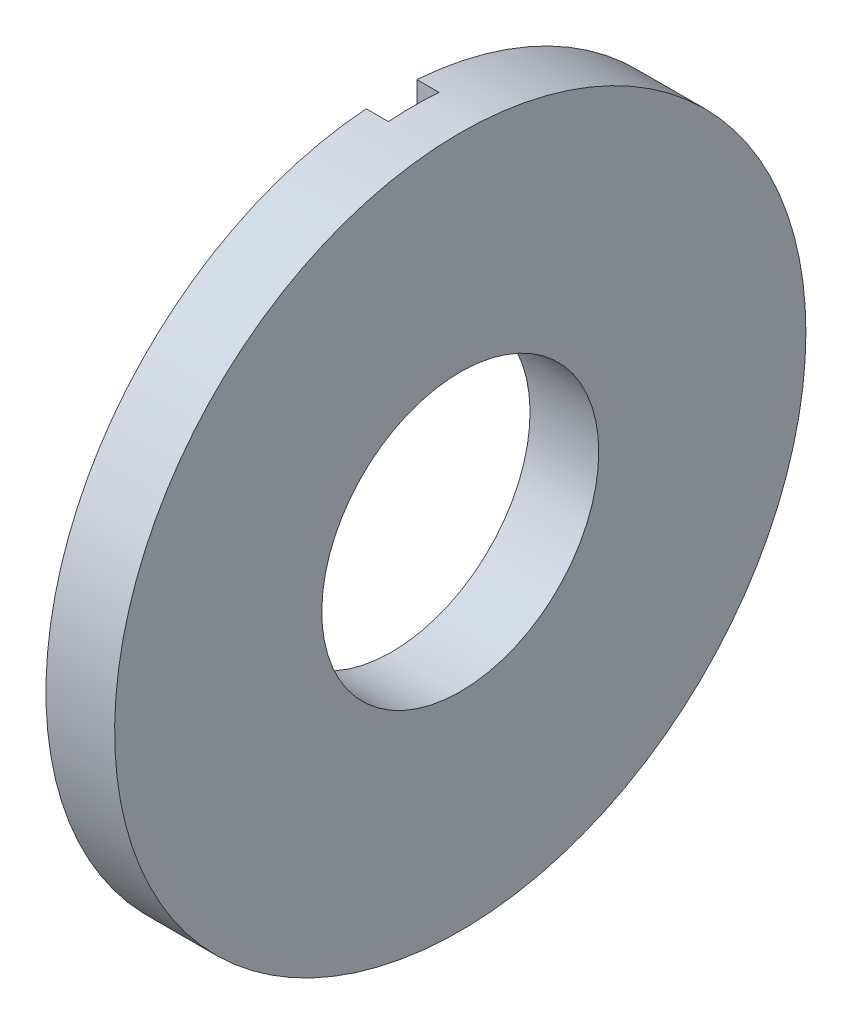
SolidWorks part; units mm, degrees
ref_plane "Front Plane" through (0, 0, 0) normal (0, 0, 1) x (1, 0, 0)
ref_plane "Top Plane" through (0, 0, 0) normal (0, 1, 0) x (1, 0, 0)
ref_plane "Right Plane" through (0, 0, 0) normal (1, 0, 0) x (0, 0, -1)
sketch "Sketch3" plane through (0, 0, 0) normal (0, 0, 1) x (1, 0, 0)
  line L0 (-0.3937, 0) -> (0.3937, 0) construction
  line L1 (0, -3.9624) -> (0, 3.9624) construction
  line L2 (0, -1.5875) -> (0, 1.5875) construction
  line L4 (0.3937, -3.9624) -> (-0.3937, -3.9624)
  line L5 (0.3937, -3.9624) -> (0.3937, 3.9624)
  line L6 (0.3937, 3.9624) -> (-0.3937, 3.9624)
  line L7 (-0.3937, -3.9624) -> (-0.3937, 3.9624)
  line L8 (0, 3.9624) -> (0, -3.9624) construction
  line L9 (0.3937, 0) -> (-0.3937, 0) construction
  point P0 (0, 0)
  point P4 (0, 0)
  point P8 (0, 0)
  point P11 (0, 0)
  dimension "Thickness" = 0.7874
sketch "Sketch1" plane through (0, 0, 0) normal (1, 0, 0) x (0, 0, -1)
  circle A0 centre (0, 0) radius 3.9624
  circle A1 centre (0, 0) radius 1.5875
extrude "Boss-Extrude1" add sketch "Sketch1" along normal mid plane 0.7874
sketch "Sketch4" plane through (-0.3937, 0, 0) normal (-1, 0, 0) x (0, 0, 1)
  line L0 (0, -3.9624) -> (0, 3.9624) construction
  point P0 (0, -1.5875)
sketch "Sketch5" plane through (-0.3937, 0, 0) normal (-1, 0, 0) x (0, 0, 1)
  line L0 (-0.2902, 0) -> (0.2902, 0)
  line L1 (0.2902, 0) -> (0.2902, 3.9624)
  line L2 (-0.2902, 0) -> (-0.2902, 3.9624)
  line L3 (-0.2902, 3.9624) -> (0.2902, 3.9624)
  circle A0 centre (0, 0) radius 3.9624 construction
  point P4 (0, 0)
extrude "Cut-Extrude1" cut sketch "Sketch5" against normal blind 0.254
equation "\"D1@Boss-Extrude1\" = \"Thickness@Sketch3\""
